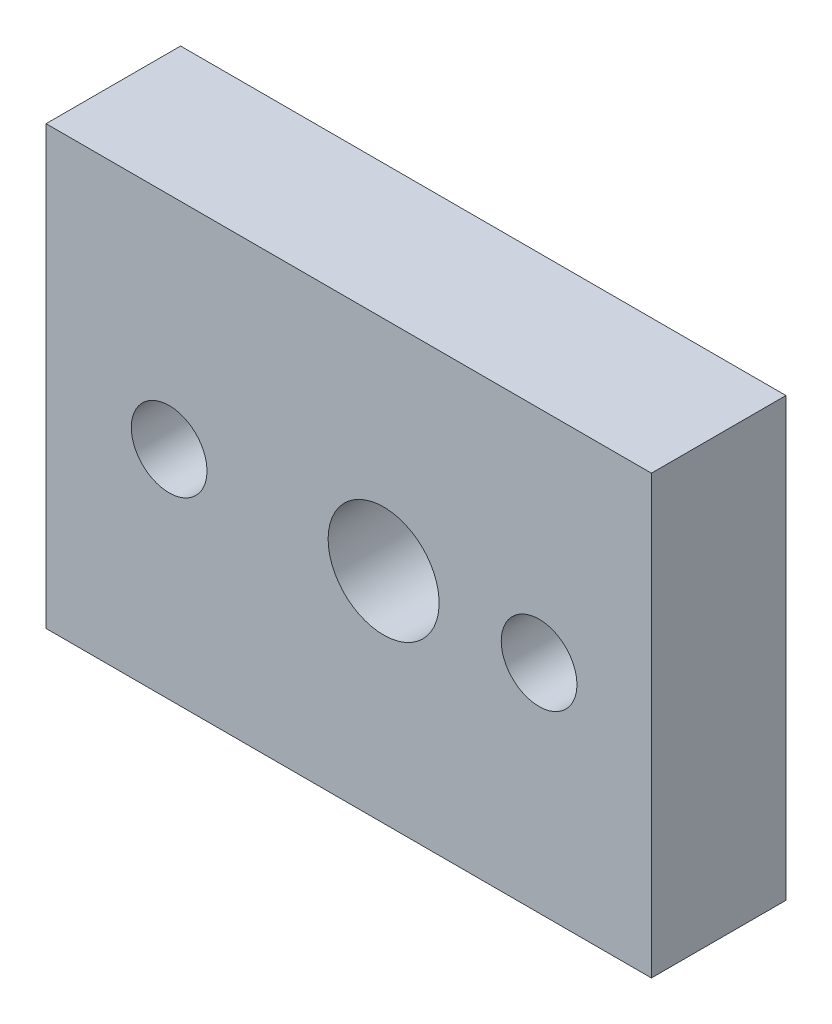
SolidWorks part; units mm, degrees
ref_plane "Plan de face" through (0, 0, 0) normal (0, 0, 1) x (1, 0, 0)
ref_plane "Plan de dessus" through (0, 0, 0) normal (0, 1, 0) x (1, 0, 0)
ref_plane "Plan de droite" through (0, 0, 0) normal (1, 0, 0) x (0, 0, -1)
sketch "Esquisse1" plane through (0, 0, 0) normal (0, 0, 1) x (1, 0, 0)
  line L1 (-18, -13) -> (18, -13)
  line L2 (-18, -13) -> (-18, 13)
  line L3 (-18, 13) -> (18, 13)
  line L4 (18, -13) -> (18, 13)
  line L5 (-18, -13) -> (18, 13) construction
  line L6 (-18, 13) -> (18, -13) construction
  point P0 (0, 0)
  dimension "D1" = 36
  dimension "D2" = 26
extrude "Boss.-Extru.1" add sketch "Esquisse1" along normal blind 8
hole_wizard "Dégagement M41" positions "Esquisse3" profile "Esquisse2" hole size "M4" standard "JIS" end condition through all
sketch "Esquisse3" plane through (0, 0, 0) normal (0, 0, -1) x (-1, 0, 0)
  point P0 (-11.3189, -0.1078)
  point P2 (10.6811, -0.105)
sketch "Esquisse2" plane through (11.3189, -0.1078, 0) normal (1, 0, 0) x (0, 1, 0)
  line L0 (0, 0) -> (0, 8)
  line L1 (0, 8) -> (2.25, 8)
  line L2 (2.25, 8) -> (2.25, 0)
  line L5 (2.25, 0) -> (0, 0)
  line L11 (0, -6.35) -> (0, 107.95) construction
  dimension "Diamètre du perçage jusqu'au prochain" = 4.5
  dimension "Profondeur du perçage jusqu'au prochain" = 8
hole_wizard "M6 Clearance Hole2" positions "Sketch6" profile "Sketch5" hole size "M6" standard "ANSI Metric" end condition through all
sketch "Sketch6" plane through (0, 0, 0) normal (0, 0, -1) x (-1, 0, 0)
  point P0 (-2.0735, 0)
sketch "Sketch5" plane through (2.0735, 0, 0) normal (1, 0, 0) x (0, 1, 0)
  line L0 (0, 0) -> (0, 8)
  line L1 (0, 8) -> (3.3, 8)
  line L2 (3.3, 8) -> (3.3, 0)
  line L5 (3.3, 0) -> (0, 0)
  line L11 (0, -6.35) -> (0, 107.95) construction
  dimension "Thru Hole Dia." = 6.6
  dimension "Thru Hole Depth" = 8
